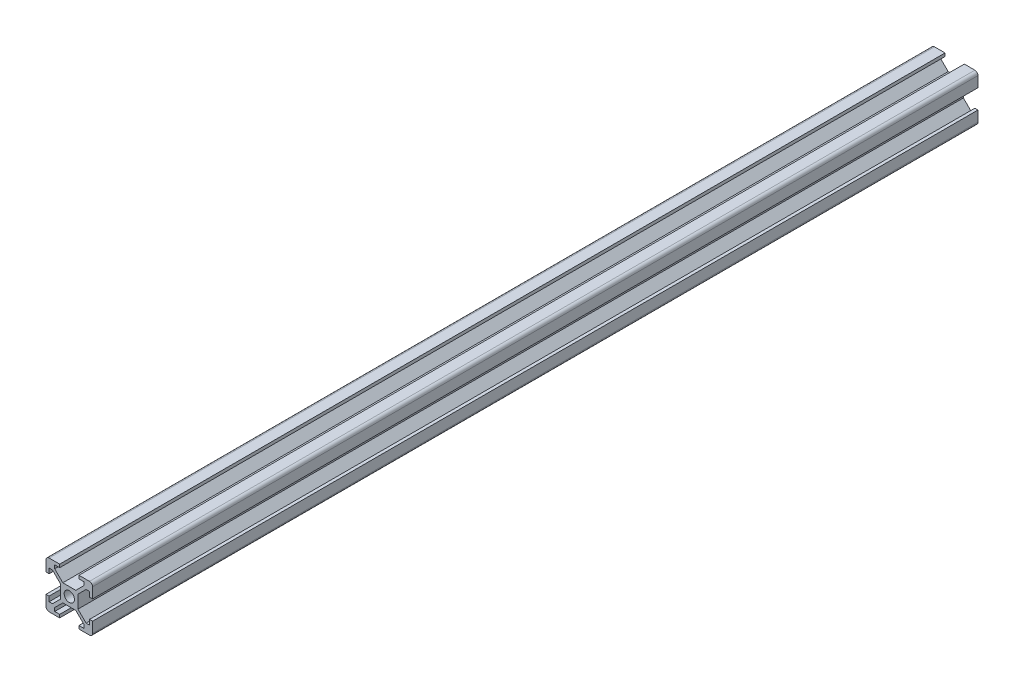
SolidWorks part; units mm, degrees
ref_plane "前视基准面" through (0, 0, 0) normal (0, 0, 1) x (1, 0, 0)
ref_plane "上视基准面" through (0, 0, 0) normal (0, 1, 0) x (1, 0, 0)
ref_plane "右视基准面" through (0, 0, 0) normal (1, 0, 0) x (0, 0, -1)
sketch "草图2" plane through (0, 0, 0) normal (0, 0, 1) x (1, 0, 0)
  line L1 (-2.0929, -2.8) -> (-4.7, -5.4071)
  line L2 (2.8, -2.0929) -> (2.8, 2.0929)
  line L3 (2.8, 2.0929) -> (5.4071, 4.7)
  line L4 (5.4071, 4.7) -> (6.5, 4.7)
  line L5 (6.5, 4.7) -> (6.5, 3.1)
  line L6 (6.5, 3.1) -> (7.5, 3.1)
  line L7 (7.5, 3.1) -> (7.5, 6.5)
  line L8 (-2.8, -2.0929) -> (-5.4071, -4.7)
  line L9 (-2.0929, 2.8) -> (2.0929, 2.8)
  line L10 (3.1, 7.5) -> (6.5, 7.5)
  line L11 (3.1, 6.5) -> (3.1, 7.5)
  line L12 (4.7, 6.5) -> (3.1, 6.5)
  line L13 (4.7, 5.4071) -> (4.7, 6.5)
  line L14 (2.0929, 2.8) -> (4.7, 5.4071)
  line L15 (-5.4071, 4.7) -> (-6.5, 4.7)
  line L16 (-6.5, 4.7) -> (-6.5, 3.1)
  line L17 (-6.5, 3.1) -> (-7.5, 3.1)
  line L18 (-7.5, 3.1) -> (-7.5, 6.5)
  line L19 (-4.7, 6.5) -> (-3.1, 6.5)
  line L20 (-3.1, 6.5) -> (-3.1, 7.5)
  line L21 (-3.1, 7.5) -> (-6.5, 7.5)
  line L22 (-4.7, 5.4071) -> (-4.7, 6.5)
  line L23 (-2.8, 2.0929) -> (-5.4071, 4.7)
  line L24 (-2.8, -2.0929) -> (-2.8, 2.0929)
  line L25 (-2.0929, 2.8) -> (-4.7, 5.4071)
  line L26 (-4.7, -5.4071) -> (-4.7, -6.5)
  line L27 (-3.1, -7.5) -> (-6.5, -7.5)
  line L28 (-3.1, -6.5) -> (-3.1, -7.5)
  line L29 (-4.7, -6.5) -> (-3.1, -6.5)
  line L30 (-7.5, -3.1) -> (-7.5, -6.5)
  line L31 (-6.5, -3.1) -> (-7.5, -3.1)
  line L32 (-6.5, -4.7) -> (-6.5, -3.1)
  line L33 (-5.4071, -4.7) -> (-6.5, -4.7)
  line L34 (2.0929, -2.8) -> (4.7, -5.4071)
  line L35 (4.7, -5.4071) -> (4.7, -6.5)
  line L36 (4.7, -6.5) -> (3.1, -6.5)
  line L37 (3.1, -6.5) -> (3.1, -7.5)
  line L38 (3.1, -7.5) -> (6.5, -7.5)
  line L39 (-2.0929, -2.8) -> (2.0929, -2.8)
  line L40 (7.5, -3.1) -> (7.5, -6.5)
  line L41 (6.5, -3.1) -> (7.5, -3.1)
  line L42 (6.5, -4.7) -> (6.5, -3.1)
  line L43 (5.4071, -4.7) -> (6.5, -4.7)
  line L44 (2.8, -2.0929) -> (5.4071, -4.7)
  arc A0 (7.5, 6.5) -> (6.5, 7.5) centre (6.5, 6.5) ccw
  arc A1 (-7.5, 6.5) -> (-6.5, 7.5) centre (-6.5, 6.5) cw
  arc A2 (-7.5, -6.5) -> (-6.5, -7.5) centre (-6.5, -6.5) ccw
  arc A3 (7.5, -6.5) -> (6.5, -7.5) centre (6.5, -6.5) cw
  circle A4 centre (0, 0) radius 1.65
  point P3 (0, -2.8)
  point P21 (7.5, 7.5)
  point P36 (0, 2.8)
  point P43 (-2.8, 0)
  point P60 (2.8, 0)
  point P61 (7.5, -7.5)
  dimension "D9" = 1
  dimension "D1" = 3.3
  dimension "D5" = 1
  dimension "D8" = 1
extrude "凸台-拉伸1" add sketch "草图2" along normal mid plane 285
